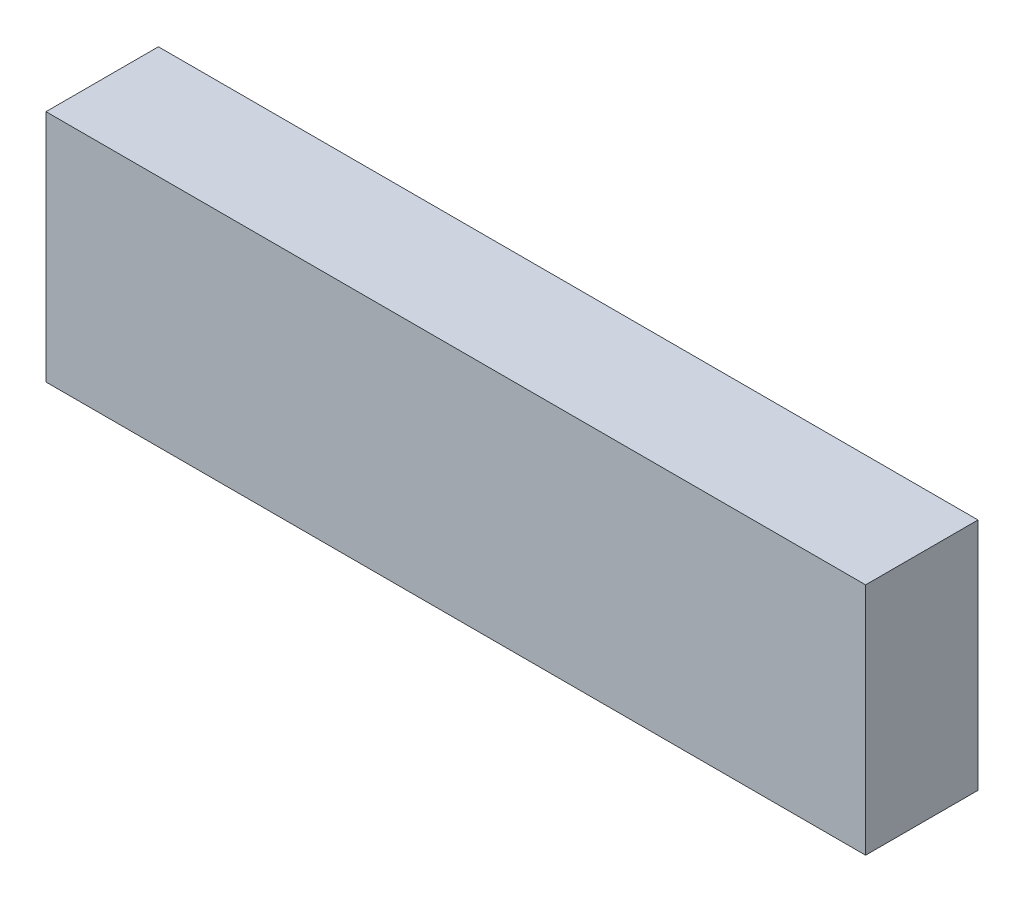
SolidWorks part; units mm, degrees
ref_plane "Front Plane" through (0, 0, 0) normal (0, 0, 1) x (1, 0, 0)
ref_plane "Top Plane" through (0, 0, 0) normal (0, 1, 0) x (1, 0, 0)
ref_plane "Right Plane" through (0, 0, 0) normal (1, 0, 0) x (0, 0, -1)
sketch "Sketch1" plane through (0, 0, 0) normal (0, 0, 1) x (1, 0, 0)
  line L1 (0, 0) -> (1.75, 0)
  line L2 (0, 0) -> (0, 0.5)
  line L3 (0, 0.5) -> (1.75, 0.5)
  line L4 (1.75, 0) -> (1.75, 0.5)
  dimension "D1" = 0.5
  dimension "D2" = 1.75
extrude "Boss-Extrude1" add sketch "Sketch1" along normal blind 0.24
